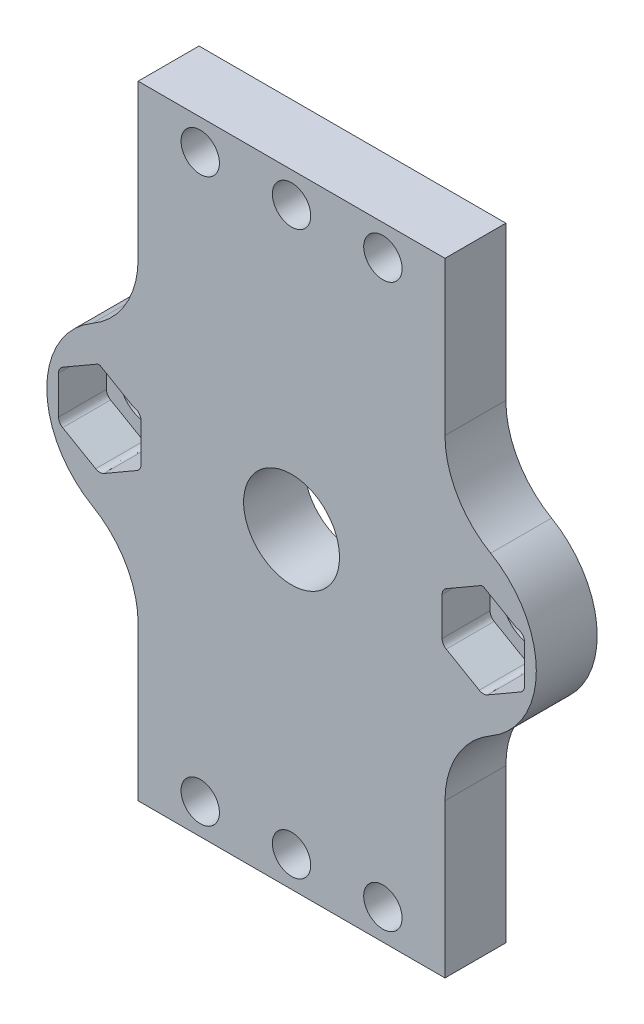
SolidWorks part; units mm, degrees
ref_plane "Front Plane" through (0, 0, 0) normal (0, 0, 1) x (1, 0, 0)
ref_plane "Top Plane" through (0, 0, 0) normal (0, 1, 0) x (1, 0, 0)
ref_plane "Right Plane" through (0, 0, 0) normal (1, 0, 0) x (0, 0, -1)
sketch "Sketch1" plane through (0, 0, 0) normal (0, 0, 1) x (1, 0, 0)
  line L0 (-33.7212, 79.5234) -> (-33.7212, 63.5212)
  line L1 (-1.7212, 63.5212) -> (-1.7212, 79.5234)
  line L2 (-1.7212, 14.5234) -> (-1.7212, 30.5256)
  line L3 (-33.7212, 14.5234) -> (-1.7212, 14.5234)
  line L4 (-33.7212, 30.5256) -> (-33.7212, 14.5234)
  line L5 (-1.7212, 79.5234) -> (-33.7212, 79.5234)
  arc A0 (-1.7212, 63.5212) -> (3.0413, 55.2723) centre (7.8038, 63.5212) ccw
  arc A1 (3.0413, 38.7745) -> (3.0413, 55.2723) centre (-1.7212, 47.0234) ccw
  arc A2 (3.0413, 38.7745) -> (-1.7212, 30.5256) centre (7.8038, 30.5256) ccw
  arc A3 (-33.7212, 30.5256) -> (-38.4837, 38.7745) centre (-43.2462, 30.5256) ccw
  arc A4 (-38.4837, 55.2723) -> (-38.4837, 38.7745) centre (-33.7212, 47.0234) ccw
  arc A5 (-38.4837, 55.2723) -> (-33.7212, 63.5212) centre (-43.2462, 63.5212) ccw
  circle A6 centre (-27.2462, 17.6984) radius 2
  circle A7 centre (-17.7212, 17.6984) radius 2
  circle A8 centre (-8.1962, 17.6984) radius 2
  circle A9 centre (2.2788, 47.0234) radius 3
  circle A10 centre (-17.7212, 47.0234) radius 5
  circle A11 centre (-37.7212, 47.0234) radius 3
  circle A12 centre (-8.1962, 76.3484) radius 2
  circle A13 centre (-17.7212, 76.3484) radius 2
  circle A14 centre (-27.2462, 76.3484) radius 2
  point P36 (0, 0)
  point P37 (0, 0)
extrude "Boss-Extrude1" add sketch "Sketch1" along normal blind 6.35
sketch "Sketch4" plane through (0, 0, 6.35) normal (0, 0, 1) x (1, 0, 0)
  line L0 (-41.5915, 49.7541) -> (-38.1509, 51.7405)
  line L1 (-42.0212, 45.037) -> (-42.0212, 49.0098)
  line L2 (-38.1509, 42.3063) -> (-41.5915, 44.2927)
  line L3 (-33.8509, 44.2927) -> (-37.2915, 42.3063)
  line L4 (-33.4212, 49.0098) -> (-33.4212, 45.037)
  line L5 (-37.6764, 51.8544) -> (-34.2364, 49.8683)
  line L6 (-42.0212, 47.0234) -> (-33.4212, 47.0234) construction
  line L7 (-37.6764, 51.8544) -> (-37.7257, 42.1912) construction
  line L8 (-1.5915, 49.7541) -> (1.8491, 51.7405)
  line L9 (-2.0212, 45.037) -> (-2.0212, 49.0098)
  line L10 (1.8491, 42.3063) -> (-1.5915, 44.2927)
  line L11 (6.1491, 44.2927) -> (2.7085, 42.3063)
  line L12 (6.5788, 49.0098) -> (6.5788, 45.037)
  line L13 (2.3236, 51.8544) -> (5.7636, 49.8683)
  line L14 (-2.0212, 47.0234) -> (6.5788, 47.0234) construction
  line L15 (2.3236, 51.8544) -> (2.2743, 42.1912) construction
  arc A0 (-33.7212, 49.6622) -> (-34.2364, 49.8683) centre (-34.2836, 49.0032) ccw
  arc A1 (6.2788, 49.6622) -> (5.7636, 49.8683) centre (5.7164, 49.0032) ccw
  spline S0 degree 3 poles (-42.0212, 49.0098) (-42.0212, 49.0099) (-42.0212, 49.0101) (-42.0212, 49.0102) (-42.0212, 49.0344) (-42.0202, 49.0595) (-42.0179, 49.0852) (-42.0066, 49.2122) (-41.9683, 49.3316) (-41.8437, 49.5473) (-41.7595, 49.6403) (-41.6552, 49.7135) (-41.634, 49.7283) (-41.6128, 49.7417) (-41.5918, 49.7539) (-41.5917, 49.754) (-41.5916, 49.754) (-41.5915, 49.7541) knots -0.293601 -0.293601 -0.293601 -0.293601 -0.293567 -0.293567 -0.293567 -0.288728 -0.288728 -0.288728 -0.264902 -0.264902 -0.241075 -0.241075 -0.241075 -0.236237 -0.236237 -0.236237 -0.236203 -0.236203 -0.236203 -0.236203 weights 1 1 1 1 1 1 1 1 1 1 1 1 1 1 1 1 1 1
  spline S1 degree 3 poles (-41.5915, 44.2927) (-41.5916, 44.2928) (-41.5917, 44.2928) (-41.5918, 44.2929) (-41.6128, 44.3051) (-41.634, 44.3184) (-41.6552, 44.3333) (-41.7595, 44.4065) (-41.8437, 44.4994) (-41.9683, 44.7152) (-42.0066, 44.8346) (-42.0179, 44.9616) (-42.0202, 44.9873) (-42.0212, 45.0124) (-42.0212, 45.0366) (-42.0212, 45.0367) (-42.0212, 45.0368) (-42.0212, 45.037) knots -0.293601 -0.293601 -0.293601 -0.293601 -0.293567 -0.293567 -0.293567 -0.288728 -0.288728 -0.288728 -0.264902 -0.264902 -0.241075 -0.241075 -0.241075 -0.236237 -0.236237 -0.236237 -0.236203 -0.236203 -0.236203 -0.236203 weights 1 1 1 1 1 1 1 1 1 1 1 1 1 1 1 1 1 1
  spline S2 degree 3 poles (-37.2915, 42.3063) (-37.2916, 42.3062) (-37.2917, 42.3061) (-37.2918, 42.3061) (-37.3129, 42.294) (-37.3351, 42.2824) (-37.3585, 42.2715) (-37.4741, 42.2177) (-37.5967, 42.1912) (-37.8458, 42.1912) (-37.9684, 42.2177) (-38.0839, 42.2715) (-38.1074, 42.2824) (-38.1296, 42.294) (-38.1506, 42.3061) (-38.1507, 42.3061) (-38.1508, 42.3062) (-38.1509, 42.3063) knots -0.293601 -0.293601 -0.293601 -0.293601 -0.293567 -0.293567 -0.293567 -0.288728 -0.288728 -0.288728 -0.264902 -0.264902 -0.241075 -0.241075 -0.241075 -0.236237 -0.236237 -0.236237 -0.236203 -0.236203 -0.236203 -0.236203 weights 1 1 1 1 1 1 1 1 1 1 1 1 1 1 1 1 1 1
  spline S3 degree 3 poles (-33.4212, 45.037) (-33.4212, 45.0368) (-33.4212, 45.0367) (-33.4212, 45.0366) (-33.4213, 45.0124) (-33.4223, 44.9873) (-33.4246, 44.9616) (-33.4358, 44.8346) (-33.4742, 44.7152) (-33.585, 44.5232) (-33.6469, 44.4482) (-33.7212, 44.3845) knots -0.293601 -0.293601 -0.293601 -0.293601 -0.293567 -0.293567 -0.293567 -0.288728 -0.288728 -0.288728 -0.264902 -0.264902 -0.246329 -0.246329 -0.246329 -0.246329 weights 1 1 1 1 1 1 1 1 1 1 1 1
  spline S4 degree 3 poles (-33.7212, 49.6622) (-33.6469, 49.5986) (-33.585, 49.5236) (-33.4742, 49.3316) (-33.4358, 49.2122) (-33.4246, 49.0852) (-33.4223, 49.0595) (-33.4213, 49.0344) (-33.4212, 49.0102) (-33.4212, 49.0101) (-33.4212, 49.0099) (-33.4212, 49.0098) knots -0.283475 -0.283475 -0.283475 -0.283475 -0.264902 -0.264902 -0.241075 -0.241075 -0.241075 -0.236237 -0.236237 -0.236237 -0.236203 -0.236203 -0.236203 -0.236203 weights 1 1 1 1 1 1 1 1 1 1 1 1
  spline S5 degree 3 poles (-38.1509, 51.7405) (-38.1509, 51.7406) (-38.1508, 51.7406) (-38.1508, 51.7407) (-38.1408, 51.7501) (-38.13, 51.7595) (-38.1186, 51.7686) (-38.0619, 51.8136) (-37.9977, 51.8445) (-37.8601, 51.8775) (-37.7889, 51.8791) (-37.718, 51.8648) (-37.7036, 51.8618) (-37.6898, 51.8583) (-37.6766, 51.8545) (-37.6765, 51.8544) (-37.6765, 51.8544) (-37.6764, 51.8544) knots -0.293601 -0.293601 -0.293601 -0.293601 -0.293567 -0.293567 -0.293567 -0.288728 -0.288728 -0.288728 -0.264902 -0.264902 -0.241075 -0.241075 -0.241075 -0.236237 -0.236237 -0.236237 -0.236203 -0.236203 -0.236203 -0.236203 weights 1 1 1 1 1 1 1 1 1 1 1 1 1 1 1 1 1 1
  spline S6 degree 3 poles (-33.7212, 44.3845) (-33.7423, 44.3665) (-33.7643, 44.3494) (-33.7873, 44.3333) (-33.8085, 44.3184) (-33.8296, 44.3051) (-33.8506, 44.2929) (-33.8507, 44.2928) (-33.8508, 44.2928) (-33.8509, 44.2927) knots -0.246329 -0.246329 -0.246329 -0.246329 -0.241075 -0.241075 -0.241075 -0.236237 -0.236237 -0.236237 -0.236203 -0.236203 -0.236203 -0.236203 weights 1 1 1 1 1 1 1 1 1 1
  spline S7 degree 3 poles (-2.0212, 49.0098) (-2.0212, 49.0099) (-2.0212, 49.0101) (-2.0212, 49.0102) (-2.0212, 49.0344) (-2.0202, 49.0595) (-2.0179, 49.0852) (-2.0066, 49.2122) (-1.9683, 49.3316) (-1.8437, 49.5473) (-1.7595, 49.6403) (-1.6552, 49.7135) (-1.634, 49.7283) (-1.6128, 49.7417) (-1.5918, 49.7539) (-1.5917, 49.754) (-1.5916, 49.754) (-1.5915, 49.7541) knots -0.293601 -0.293601 -0.293601 -0.293601 -0.293567 -0.293567 -0.293567 -0.288728 -0.288728 -0.288728 -0.264902 -0.264902 -0.241075 -0.241075 -0.241075 -0.236237 -0.236237 -0.236237 -0.236203 -0.236203 -0.236203 -0.236203 weights 1 1 1 1 1 1 1 1 1 1 1 1 1 1 1 1 1 1
  spline S8 degree 3 poles (-1.5915, 44.2927) (-1.5916, 44.2928) (-1.5917, 44.2928) (-1.5918, 44.2929) (-1.6128, 44.3051) (-1.634, 44.3184) (-1.6552, 44.3333) (-1.7595, 44.4065) (-1.8437, 44.4994) (-1.9683, 44.7152) (-2.0066, 44.8346) (-2.0179, 44.9616) (-2.0202, 44.9873) (-2.0212, 45.0124) (-2.0212, 45.0366) (-2.0212, 45.0367) (-2.0212, 45.0368) (-2.0212, 45.037) knots -0.293601 -0.293601 -0.293601 -0.293601 -0.293567 -0.293567 -0.293567 -0.288728 -0.288728 -0.288728 -0.264902 -0.264902 -0.241075 -0.241075 -0.241075 -0.236237 -0.236237 -0.236237 -0.236203 -0.236203 -0.236203 -0.236203 weights 1 1 1 1 1 1 1 1 1 1 1 1 1 1 1 1 1 1
  spline S9 degree 3 poles (2.7085, 42.3063) (2.7084, 42.3062) (2.7083, 42.3061) (2.7082, 42.3061) (2.6871, 42.294) (2.6649, 42.2824) (2.6415, 42.2715) (2.5259, 42.2177) (2.4033, 42.1912) (2.1542, 42.1912) (2.0316, 42.2177) (1.9161, 42.2715) (1.8926, 42.2824) (1.8704, 42.294) (1.8494, 42.3061) (1.8493, 42.3061) (1.8492, 42.3062) (1.8491, 42.3063) knots -0.293601 -0.293601 -0.293601 -0.293601 -0.293567 -0.293567 -0.293567 -0.288728 -0.288728 -0.288728 -0.264902 -0.264902 -0.241075 -0.241075 -0.241075 -0.236237 -0.236237 -0.236237 -0.236203 -0.236203 -0.236203 -0.236203 weights 1 1 1 1 1 1 1 1 1 1 1 1 1 1 1 1 1 1
  spline S10 degree 3 poles (6.5788, 45.037) (6.5788, 45.0368) (6.5788, 45.0367) (6.5788, 45.0366) (6.5787, 45.0124) (6.5777, 44.9873) (6.5754, 44.9616) (6.5642, 44.8346) (6.5258, 44.7152) (6.415, 44.5232) (6.3531, 44.4482) (6.2788, 44.3845) knots -0.293601 -0.293601 -0.293601 -0.293601 -0.293567 -0.293567 -0.293567 -0.288728 -0.288728 -0.288728 -0.264902 -0.264902 -0.246329 -0.246329 -0.246329 -0.246329 weights 1 1 1 1 1 1 1 1 1 1 1 1
  spline S11 degree 3 poles (6.2788, 49.6622) (6.3531, 49.5986) (6.415, 49.5236) (6.5258, 49.3316) (6.5642, 49.2122) (6.5754, 49.0852) (6.5777, 49.0595) (6.5787, 49.0344) (6.5788, 49.0102) (6.5788, 49.0101) (6.5788, 49.0099) (6.5788, 49.0098) knots -0.283475 -0.283475 -0.283475 -0.283475 -0.264902 -0.264902 -0.241075 -0.241075 -0.241075 -0.236237 -0.236237 -0.236237 -0.236203 -0.236203 -0.236203 -0.236203 weights 1 1 1 1 1 1 1 1 1 1 1 1
  spline S12 degree 3 poles (1.8491, 51.7405) (1.8491, 51.7406) (1.8492, 51.7406) (1.8492, 51.7407) (1.8592, 51.7501) (1.87, 51.7595) (1.8814, 51.7686) (1.9381, 51.8136) (2.0023, 51.8445) (2.1399, 51.8775) (2.2111, 51.8791) (2.282, 51.8648) (2.2964, 51.8618) (2.3102, 51.8583) (2.3234, 51.8545) (2.3235, 51.8544) (2.3235, 51.8544) (2.3236, 51.8544) knots -0.293601 -0.293601 -0.293601 -0.293601 -0.293567 -0.293567 -0.293567 -0.288728 -0.288728 -0.288728 -0.264902 -0.264902 -0.241075 -0.241075 -0.241075 -0.236237 -0.236237 -0.236237 -0.236203 -0.236203 -0.236203 -0.236203 weights 1 1 1 1 1 1 1 1 1 1 1 1 1 1 1 1 1 1
  spline S13 degree 3 poles (6.2788, 44.3845) (6.2577, 44.3665) (6.2357, 44.3494) (6.2127, 44.3333) (6.1915, 44.3184) (6.1704, 44.3051) (6.1494, 44.2929) (6.1493, 44.2928) (6.1492, 44.2928) (6.1491, 44.2927) knots -0.246329 -0.246329 -0.246329 -0.246329 -0.241075 -0.241075 -0.241075 -0.236237 -0.236237 -0.236237 -0.236203 -0.236203 -0.236203 -0.236203 weights 1 1 1 1 1 1 1 1 1 1
  point P19 (-37.7212, 47.0234)
  point P20 (-37.7212, 47.0234)
  point P21 (2.2788, 47.0234)
  point P43 (2.2788, 47.0234)
  point P44 (0, 0)
  point P45 (0, 0)
extrude "Cut-Extrude1" cut sketch "Sketch4" against normal blind 5
